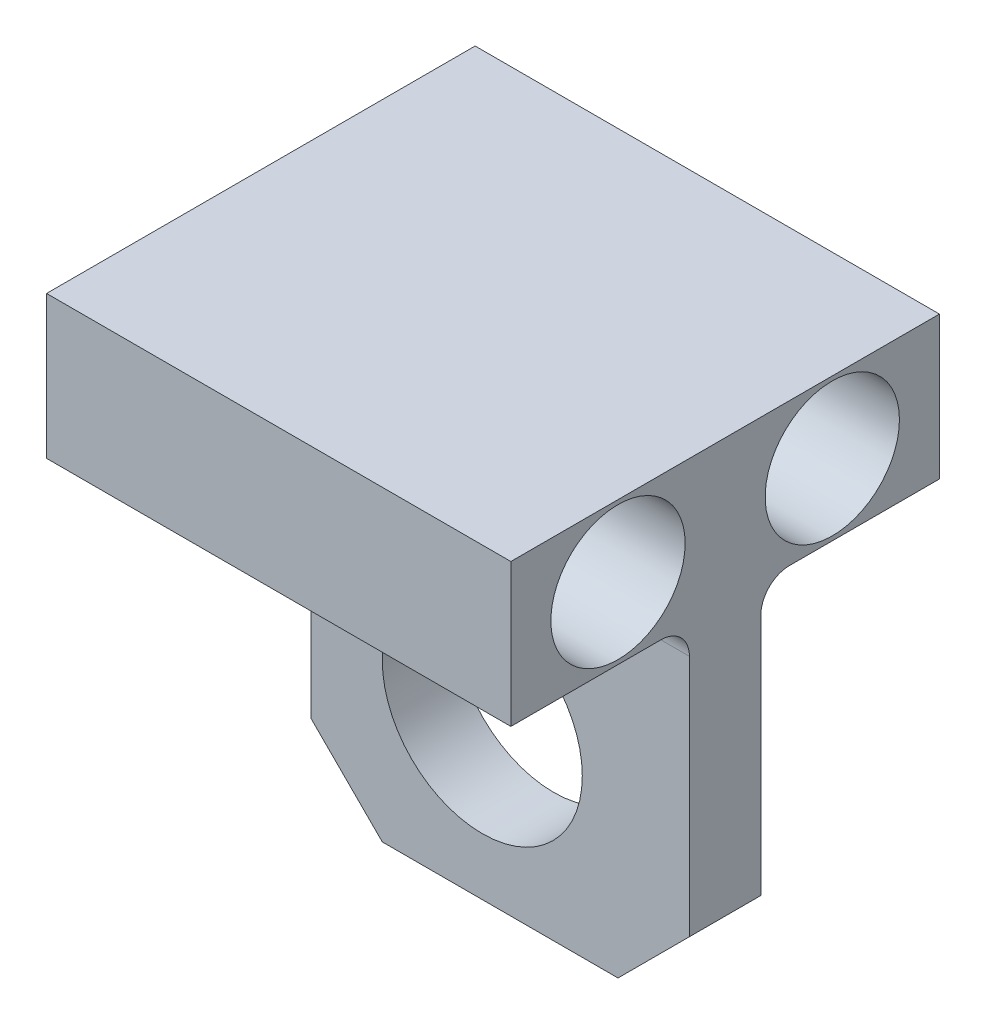
SolidWorks part; units mm, degrees
material "45#"
ref_plane "前视" through (0, 0, 0) normal (0, 0, 1) x (1, 0, 0)
ref_plane "上视" through (0, 0, 0) normal (0, 1, 0) x (1, 0, 0)
ref_plane "右视" through (0, 0, 0) normal (1, 0, 0) x (0, 0, -1)
sketch "草图1" plane through (0, 0, 0) normal (1, 0, 0) x (0, 0, -1)
  line L1 (-15, -17) -> (15, -17)
  line L2 (-15, -17) -> (-15, 17)
  line L3 (-15, 17) -> (15, 17)
  line L4 (15, -17) -> (15, 17)
  line L5 (-15, -17) -> (15, 17) construction
  line L6 (-15, 17) -> (15, -17) construction
  point P0 (0, 0)
  dimension "D1" = 30
  dimension "D2" = 34
extrude "凸台-拉伸1" add sketch "草图1" along normal mid plane 32.5
sketch "草图2" plane through (16.25, 0, 0) normal (1, 0, 0) x (0, 0, -1)
  line L1 (15, -17) -> (2.5, -17)
  line L2 (15, -17) -> (15, 7)
  line L3 (15, 7) -> (2.5, 7)
  line L4 (2.5, -17) -> (2.5, 7)
  line L5 (15, 17) -> (-15, 17) construction
  line L6 (0, 17) -> (0, 10.9396) construction
  line L7 (-2.5, -17) -> (-2.5, 7)
  line L8 (-15, 7) -> (-2.5, 7)
  line L9 (-15, -17) -> (-15, 7)
  line L10 (-15, -17) -> (-2.5, -17)
  dimension "D1" = 5
  dimension "D2" = 10
extrude "切除-拉伸1" cut sketch "草图2" against normal through all
sketch "草图5" plane through (0, 17.5, -15) normal (0, 0, 1) x (1, 0, 0)
  line L0 (-16.25, -10.5) -> (16.25, -10.5) construction
  line L1 (-16.25, -34.5) -> (-10.25, -34.5)
  line L2 (-16.25, -34.5) -> (-16.25, -10.5)
  line L3 (-16.25, -10.5) -> (-10.25, -10.5)
  line L4 (-10.25, -34.5) -> (-10.25, -10.5)
  line L5 (-16.25, -0.5) -> (-16.25, -10.5) construction
  dimension "D1" = 6
extrude "切除-拉伸2" cut sketch "草图5" along normal through all
hole_wizard "孔1" positions "草图4" profile "草图3" legacy end condition through all
sketch "草图4" plane through (0, 0, 15) normal (0, 0, 1) x (1, 0, 0)
  line L0 (16.25, 17) -> (-16.25, 17) construction
  line L3 (-16.25, 17) -> (-16.25, 7) construction
  point P0 (1.75, -6)
  dimension "D1" = 23
  dimension "D2" = 18
sketch "草图3" plane through (1.75, -6, 15) normal (1, 0, 0) x (0, -1, 0)
  line L0 (0, 0) -> (0, 30)
  line L1 (0, 30) -> (7, 30)
  line L2 (7, 30) -> (7, 0)
  line L3 (7, 0) -> (0, 0)
  line L4 (0, 110) -> (0, -10) construction
  dimension "直径" = 14
  dimension "深度" = 30
hole_wizard "打孔尺寸根据内六角圆柱头螺钉的类型1" positions "草图7" profile "草图6" counterbore size "M5" standard "Gb" end condition through all
sketch "草图7" plane through (16.25, 0, 0) normal (1, 0, 0) x (0, 0, -1)
  line L0 (15, 12) -> (0, 12) construction
  line L1 (15, 7) -> (15, 17) construction
  line L2 (0, 12) -> (0, 17) construction
  line L3 (15, 17) -> (-15, 17) construction
  point P0 (7.5, 12)
  point P14 (-7.5, 12)
  dimension "D1" = 15
sketch "草图6" plane through (16.25, 12, -7.5) normal (0, 1, 0) x (0, 0, -1)
  line L0 (0, 0) -> (0, 32.5)
  line L1 (0, 32.5) -> (2.75, 32.5)
  line L3 (2.75, 32.5) -> (2.75, 7)
  line L4 (2.75, 7) -> (4.7, 7)
  line L5 (4.7, 7) -> (4.7, 0)
  line L7 (4.7, 0) -> (0, 0)
  line L11 (0, -6.35) -> (0, 107.95) construction
  dimension "通孔孔直径" = 5.5
  dimension "通孔孔深度" = 32.5
  dimension "柱形沉头孔直径" = 9.4
  dimension "柱形沉头孔深度" = 7
fillet "圆角1" radius 2 2 edges at (3, 7, -2.5) (3, 7, 2.5)
chamfer "倒角1" distance 5 angle 45 2 edges at (16.25, -17, 0) (-10.25, -17, 0)
